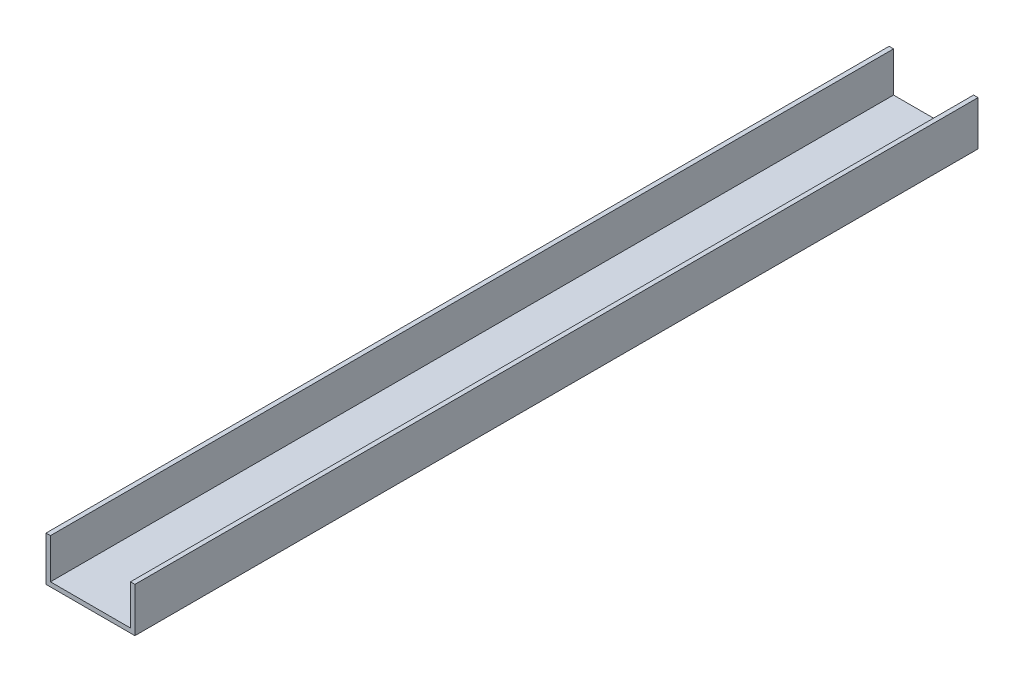
SolidWorks part; units mm, degrees
ref_plane "Piano frontale" through (0, 0, 0) normal (0, 0, 1) x (1, 0, 0)
ref_plane "Piano superiore" through (0, 0, 0) normal (0, 1, 0) x (1, 0, 0)
ref_plane "Piano destro" through (0, 0, 0) normal (1, 0, 0) x (0, 0, -1)
sketch "Schizzo1" plane through (0, 0, 0) normal (0, 0, 1) x (1, 0, 0)
  line L0 (-22.9867, -3.314) -> (37.0133, -3.314)
  line L1 (37.0133, -3.314) -> (37.0133, 26.686)
  line L2 (37.0133, 26.686) -> (34.0133, 26.686)
  line L3 (34.0133, 26.686) -> (34.0133, -0.314)
  line L4 (34.0133, -0.314) -> (-19.9867, -0.314)
  line L5 (-19.9867, -0.314) -> (-19.9867, 26.686)
  line L6 (-19.9867, 26.686) -> (-22.9867, 26.686)
  line L7 (-22.9867, 26.686) -> (-22.9867, -3.314)
  point P5 (-19.9867, 13.186)
  dimension "D1" = 60
  dimension "D2" = 30
  dimension "D3" = 3
  dimension "D4" = 3
extrude "Estrusione-Estrusione1" add sketch "Schizzo1" along normal blind 569
